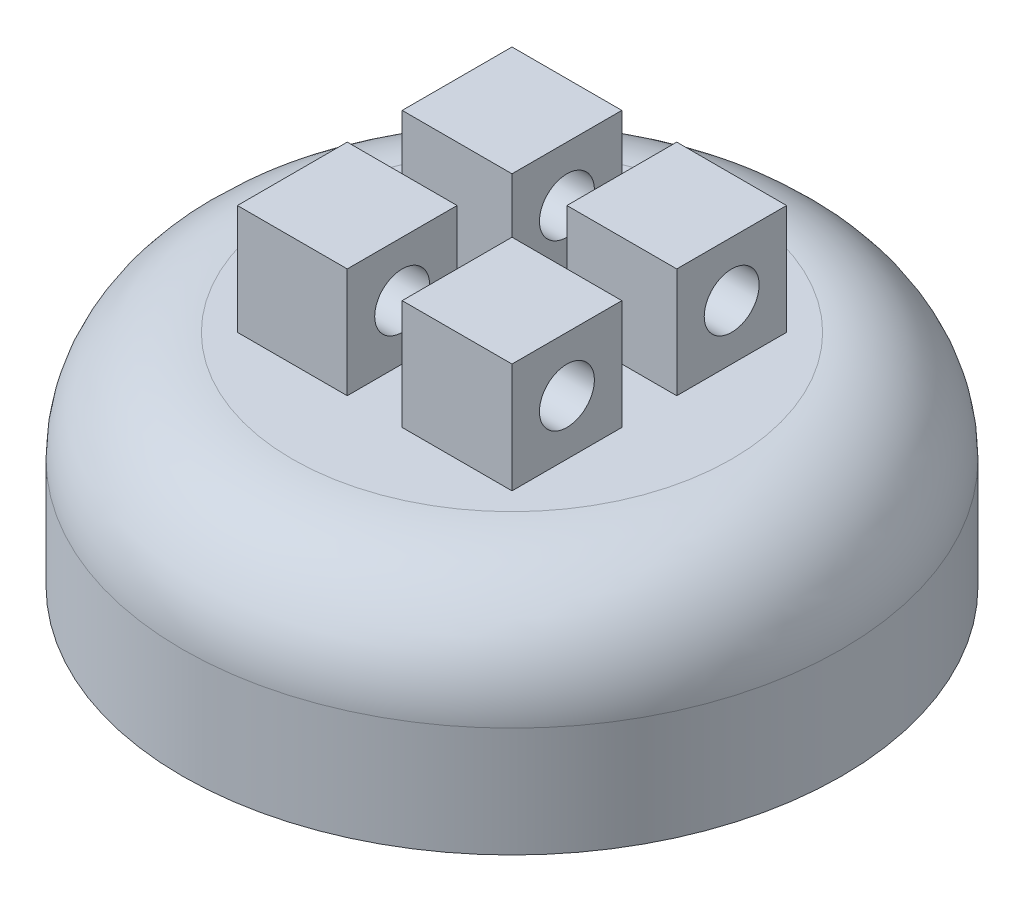
SolidWorks part; units mm, degrees
ref_plane "Front Plane" through (0, 0, 0) normal (0, 0, 1) x (1, 0, 0)
ref_plane "Top Plane" through (0, 0, 0) normal (0, 1, 0) x (1, 0, 0)
ref_plane "Right Plane" through (0, 0, 0) normal (1, 0, 0) x (0, 0, -1)
sketch "Sketch2" plane through (0, 0, 0) normal (0, 1, 0) x (1, 0, 0)
  circle A0 centre (0, 0) radius 76.2
  dimension "D1" = 152.4
extrude "Boss-Extrude2" add sketch "Sketch2" along normal blind 50.8
fillet "Fillet1" radius 25.4 1 edges at (0, 50.8, 76.2)
sketch "Sketch3" plane through (0, 50.8, 0) normal (0, 1, 0) x (1, 0, 0)
  line L0 (0, 50.8) -> (0, -50.8) construction
  line L1 (-50.8, 0) -> (50.8, 0) construction
  line L2 (-31.75, 31.75) -> (-31.75, 6.35)
  line L3 (-31.75, 6.35) -> (-6.35, 6.35)
  line L4 (-6.35, 6.35) -> (-6.35, 31.75)
  line L5 (-6.35, 31.75) -> (-31.75, 31.75)
  line L6 (6.35, 31.75) -> (6.35, 6.35)
  line L7 (6.35, 6.35) -> (31.75, 6.35)
  line L8 (31.75, 6.35) -> (31.75, 31.75)
  line L9 (31.75, 31.75) -> (6.35, 31.75)
  line L10 (-31.75, -6.35) -> (-6.35, -6.35)
  line L11 (-6.35, -6.35) -> (-6.35, -31.75)
  line L12 (-6.35, -31.75) -> (-31.75, -31.75)
  line L13 (-31.75, -31.75) -> (-31.75, -6.35)
  line L14 (6.35, -6.35) -> (31.75, -6.35)
  line L15 (31.75, -6.35) -> (31.75, -31.75)
  line L16 (31.75, -31.75) -> (6.35, -31.75)
  line L17 (6.35, -31.75) -> (6.35, -6.35)
  circle A0 centre (0, 0) radius 50.8 construction
  dimension "D1" = 25.4
  dimension "D2" = 25.4
  dimension "D3" = 25.4
  dimension "D4" = 25.4
  dimension "D5" = 6.35
  dimension "D6" = 6.35
  dimension "D7" = 6.35
  dimension "D8" = 25.4
  dimension "D9" = 25.4
  dimension "D10" = 25.4
  dimension "D11" = 25.4
  dimension "D12" = 6.35
  dimension "D13" = 6.35
  dimension "D14" = 6.35
  dimension "D15" = 6.35
  dimension "D16" = 6.35
extrude "Boss-Extrude3" add sketch "Sketch3" along normal blind 25.4
sketch "Sketch5" plane through (-31.75, 0, 0) normal (-1, 0, 0) x (0, 0, 1)
  line L0 (-19.05, 76.2) -> (-19.05, 50.8) construction
  line L1 (-31.75, 76.2) -> (-6.35, 76.2) construction
  line L2 (-31.75, 50.8) -> (-6.35, 50.8) construction
  line L3 (-31.75, 63.5) -> (-6.35, 63.5) construction
  line L4 (-31.75, 76.2) -> (-31.75, 50.8) construction
  line L5 (-6.35, 76.2) -> (-6.35, 50.8) construction
  circle A0 centre (-19.05, 63.5) radius 6.35
  point P14 (-19.05, 63.5)
  dimension "D1" = 12.7
extrude "Cut-Extrude2" cut sketch "Sketch5" against normal up to surface (63.5 mm away) up to face at (31.75, 63.5, -19.05)
sketch "Sketch6" plane through (-31.75, 0, 0) normal (-1, 0, 0) x (0, 0, 1)
  line L0 (6.35, 63.5) -> (31.75, 63.5) construction
  line L1 (6.35, 76.2) -> (6.35, 50.8) construction
  line L2 (31.75, 76.2) -> (31.75, 50.8) construction
  line L3 (19.05, 76.2) -> (19.05, 50.8) construction
  line L4 (6.35, 76.2) -> (31.75, 76.2) construction
  line L5 (6.35, 50.8) -> (31.75, 50.8) construction
  circle A0 centre (19.05, 63.5) radius 6.35
  point P14 (19.05, 63.5)
  dimension "D1" = 12.7
extrude "Cut-Extrude3" cut sketch "Sketch6" against normal up to surface (63.5 mm away) up to face at (31.75, 63.5, 19.05)
ref_plane "Plane1" through (0, 0, 76.2) normal (0, 0, 1) x (1, 0, 0)
